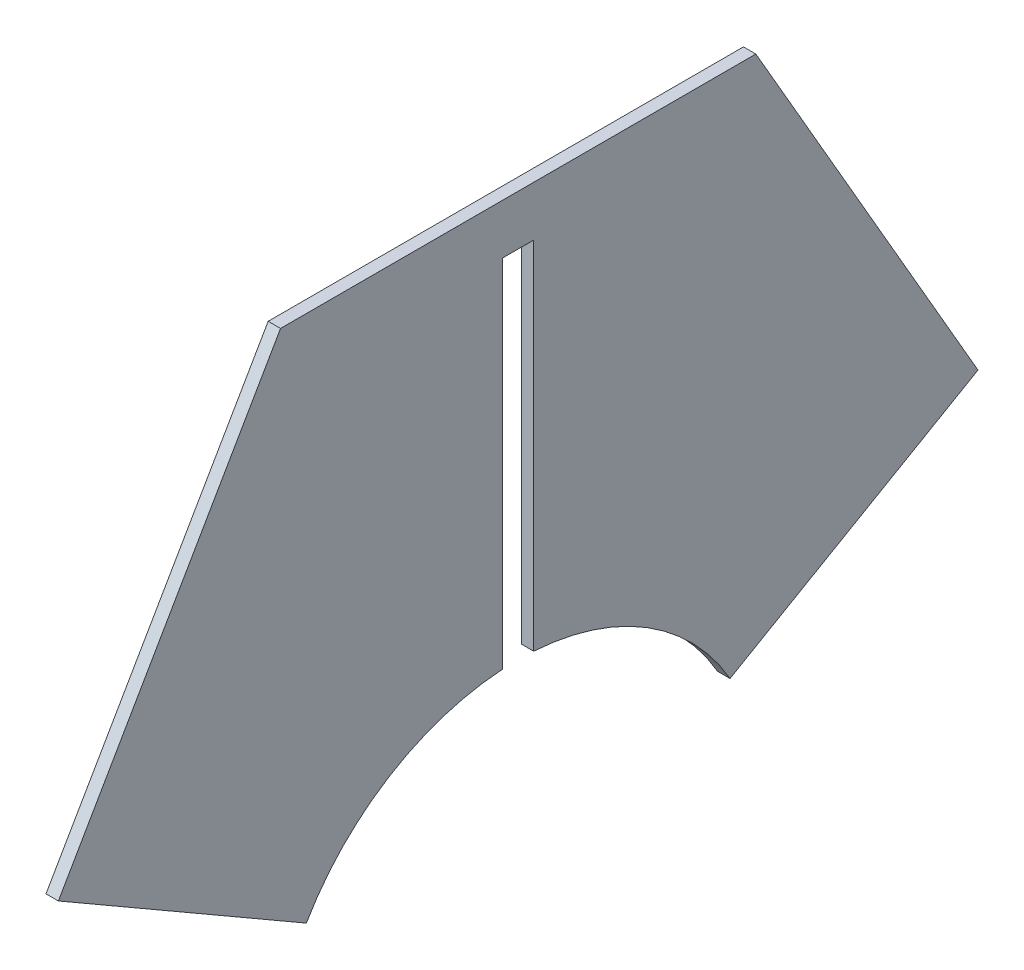
SolidWorks part; units mm, degrees
ref_plane "Plan de face" through (0, 0, 0) normal (0, 0, 1) x (1, 0, 0)
ref_plane "Plan de dessus" through (0, 0, 0) normal (0, 1, 0) x (1, 0, 0)
ref_plane "Plan de droite" through (0, 0, 0) normal (1, 0, 0) x (0, 0, -1)
sketch "Esquisse1" plane through (0, 0, 0) normal (1, 0, 0) x (0, 0, -1)
  line L0 (0, 0) -> (0, 78.8416) construction
  line L1 (0, 78.8416) -> (-5, 78.8416) construction
  line L2 (0, 78.8416) -> (5, 78.8416) construction
  line L3 (-68.416, 39.5) -> (-148.5, 85.7365)
  line L4 (-148.5, 85.7365) -> (-76.7564, 210)
  line L5 (-76.7564, 210) -> (76.7564, 210)
  line L6 (76.7564, 210) -> (148.5, 85.7365)
  line L7 (148.5, 85.7365) -> (68.416, 39.5)
  line L8 (-5, 78.8416) -> (-5, 193.8416)
  line L9 (-5, 193.8416) -> (5, 193.8416)
  line L10 (5, 193.8416) -> (5, 78.8416)
  line L11 (0, 0) -> (68.416, 39.5) construction
  line L12 (-68.416, 39.5) -> (0, 0) construction
  line L13 (0, 78.8416) -> (0, 193.8416) construction
  line L14 (0, 193.8416) -> (0, 210) construction
  line L16 (-148.5, 210) -> (148.5, 210) construction
  line L17 (-148.5, 210) -> (-148.5, 0) construction
  line L18 (-148.5, 0) -> (148.5, 0) construction
  line L19 (148.5, 210) -> (148.5, 0) construction
  arc A0 (-68.416, 39.5) -> (-5, 78.8416) centre (0, 0) cw
  arc A1 (68.416, 39.5) -> (5, 78.8416) centre (0, 0) ccw
  point P12 (0, 0)
  point P20 (139.9572, 80.8044)
  point P21 (0, 114.3139)
  point P22 (-35.5883, 210)
  point P23 (0, 0)
  point P24 (-194.0162, 112.0153)
  point P25 (-148.5, 85.4305)
  point P26 (0, 0)
  dimension "D5" = 79
  dimension "D1" = 60
  dimension "D2" = 60
  dimension "D3" = 297
  dimension "D4" = 210
  dimension "D6" = 10
  dimension "D7" = 115
extrude "Boss.-Extru.1" add sketch "Esquisse1" along normal blind 4
